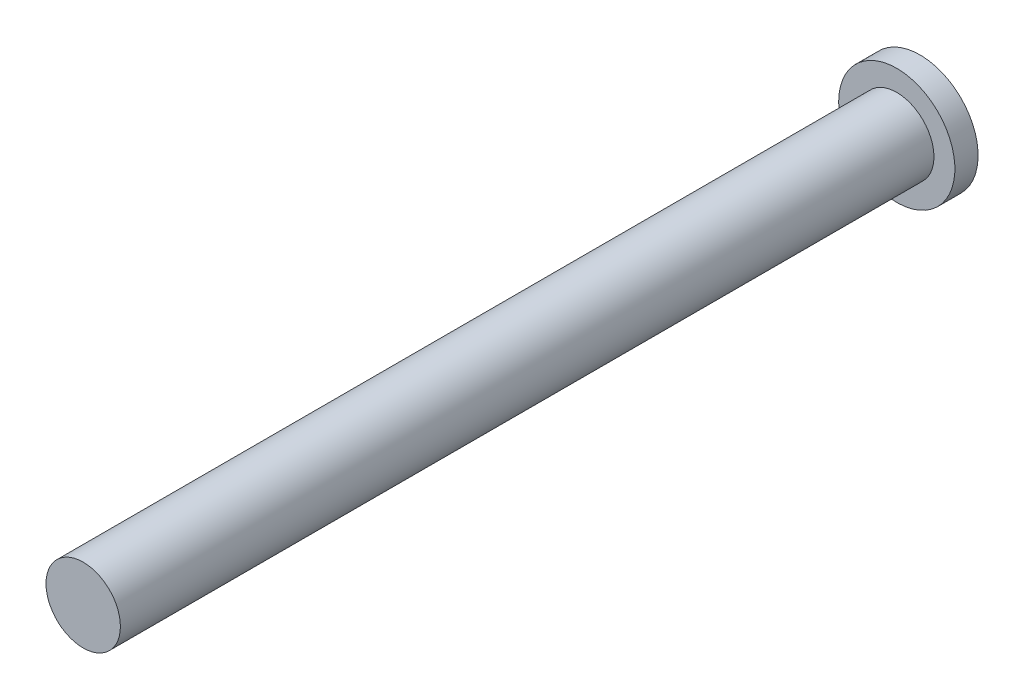
SolidWorks part; units mm, degrees
ref_plane "Front Plane" through (0, 0, 0) normal (0, 0, 1) x (1, 0, 0)
ref_plane "Top Plane" through (0, 0, 0) normal (0, 1, 0) x (1, 0, 0)
ref_plane "Right Plane" through (0, 0, 0) normal (1, 0, 0) x (0, 0, -1)
sketch "Sketch2" plane through (0, 0, 0) normal (0, 0, 1) x (1, 0, 0)
  circle A0 centre (0, 0) radius 1.6
extrude "Boss-Extrude1" add sketch "Sketch2" along normal blind 35
sketch "Sketch4" plane through (0, 0, 0) normal (0, 0, -1) x (-1, 0, 0)
  circle A0 centre (0, 0) radius 2.5
extrude "Boss-Extrude2" add sketch "Sketch4" along normal blind 1
